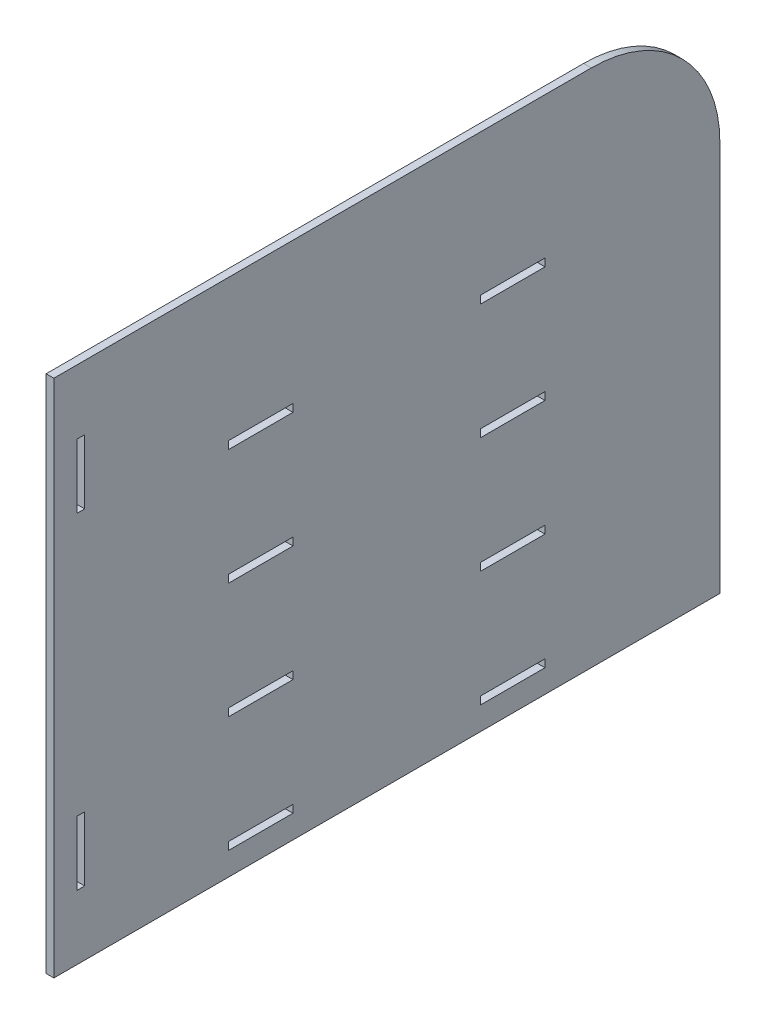
SolidWorks part; units mm, degrees
material "Maple"
ref_plane "Front Plane" through (0, 0, 0) normal (0, 0, 1) x (1, 0, 0)
ref_plane "Top Plane" through (0, 0, 0) normal (0, 1, 0) x (1, 0, 0)
ref_plane "Right Plane" through (0, 0, 0) normal (1, 0, 0) x (0, 0, -1)
sketch "Sketch1" plane through (0, 0, 0) normal (1, 0, 0) x (0, 0, -1)
  line L0 (-155.8318, -134.8488) -> (-414.8318, -134.8488) construction
  line L1 (-414.8318, 67.1512) -> (3.1682, 67.1512)
  line L2 (-414.8318, 67.1512) -> (-414.8318, -336.8488)
  line L3 (-414.8318, -336.8488) -> (103.1682, -336.8488)
  line L4 (103.1682, -32.8488) -> (103.1682, -336.8488)
  line L5 (-414.8318, 67.1512) -> (103.1682, -336.8488) construction
  line L6 (-414.8318, -336.8488) -> (103.1682, 67.1512) construction
  line L7 (-396.8318, 17.1512) -> (-390.8318, 17.1512)
  line L8 (-396.8318, 17.1512) -> (-396.8318, -32.8488)
  line L9 (-396.8318, -32.8488) -> (-390.8318, -32.8488)
  line L10 (-390.8318, 17.1512) -> (-390.8318, -32.8488)
  line L11 (-396.8318, -236.8488) -> (-390.8318, -236.8488)
  line L12 (-390.8318, -286.8488) -> (-390.8318, -236.8488)
  line L13 (-396.8318, -286.8488) -> (-390.8318, -286.8488)
  line L14 (-396.8318, -286.8488) -> (-396.8318, -236.8488)
  line L15 (-155.8318, -134.8488) -> (-155.8318, -336.8488) construction
  line L16 (-278.8318, -312.8488) -> (-228.8318, -312.8488)
  line L17 (-278.8318, -312.8488) -> (-278.8318, -318.8488)
  line L18 (-278.8318, -318.8488) -> (-228.8318, -318.8488)
  line L19 (-228.8318, -312.8488) -> (-228.8318, -318.8488)
  line L20 (-278.8318, -312.8488) -> (-228.8318, -318.8488) construction
  line L21 (-278.8318, -318.8488) -> (-228.8318, -312.8488) construction
  line L22 (-32.8318, -318.8488) -> (-82.8318, -318.8488)
  line L23 (-82.8318, -312.8488) -> (-82.8318, -318.8488)
  line L24 (-32.8318, -312.8488) -> (-82.8318, -312.8488)
  line L25 (-32.8318, -312.8488) -> (-32.8318, -318.8488)
  line L26 (-278.8318, -222.8488) -> (-278.8318, -228.8488)
  line L27 (-278.8318, -222.8488) -> (-228.8318, -222.8488)
  line L28 (-228.8318, -222.8488) -> (-228.8318, -228.8488)
  line L29 (-278.8318, -228.8488) -> (-228.8318, -228.8488)
  line L30 (-32.8318, -228.8488) -> (-82.8318, -228.8488)
  line L31 (-82.8318, -222.8488) -> (-82.8318, -228.8488)
  line L32 (-32.8318, -222.8488) -> (-82.8318, -222.8488)
  line L33 (-32.8318, -222.8488) -> (-32.8318, -228.8488)
  line L34 (-278.8318, -132.8488) -> (-278.8318, -138.8488)
  line L35 (-278.8318, -132.8488) -> (-228.8318, -132.8488)
  line L36 (-228.8318, -132.8488) -> (-228.8318, -138.8488)
  line L37 (-278.8318, -138.8488) -> (-228.8318, -138.8488)
  line L38 (-32.8318, -138.8488) -> (-82.8318, -138.8488)
  line L39 (-82.8318, -132.8488) -> (-82.8318, -138.8488)
  line L40 (-32.8318, -132.8488) -> (-82.8318, -132.8488)
  line L41 (-32.8318, -132.8488) -> (-32.8318, -138.8488)
  line L42 (-278.8318, -42.8488) -> (-278.8318, -48.8488)
  line L43 (-278.8318, -42.8488) -> (-228.8318, -42.8488)
  line L44 (-228.8318, -42.8488) -> (-228.8318, -48.8488)
  line L45 (-278.8318, -48.8488) -> (-228.8318, -48.8488)
  line L46 (-32.8318, -48.8488) -> (-82.8318, -48.8488)
  line L47 (-82.8318, -42.8488) -> (-82.8318, -48.8488)
  line L48 (-32.8318, -42.8488) -> (-82.8318, -42.8488)
  line L49 (-32.8318, -42.8488) -> (-32.8318, -48.8488)
  arc A0 (103.1682, -32.8488) -> (3.1682, 67.1512) centre (3.1682, -32.8488) ccw
  point P0 (-155.8318, -134.8488)
  point P18 (-253.8318, -315.8488)
  dimension "D3" = 100
  dimension "D1" = 404
  dimension "D2" = 518
  dimension "D4" = 50
  dimension "D5" = 18
  dimension "D6" = 6
  dimension "D7" = 50
  dimension "D8" = 18
  dimension "D9" = 136
  dimension "D10" = 50
  dimension "D11" = 6
  dimension "D13" = 136
  dimension "D14" = 136
  dimension "D15" = 18
  dimension "D16" = 84
  dimension "D17" = 50
  dimension "D12" = 4
extrude "Boss-Extrude1" add sketch "Sketch1" along normal blind 6
